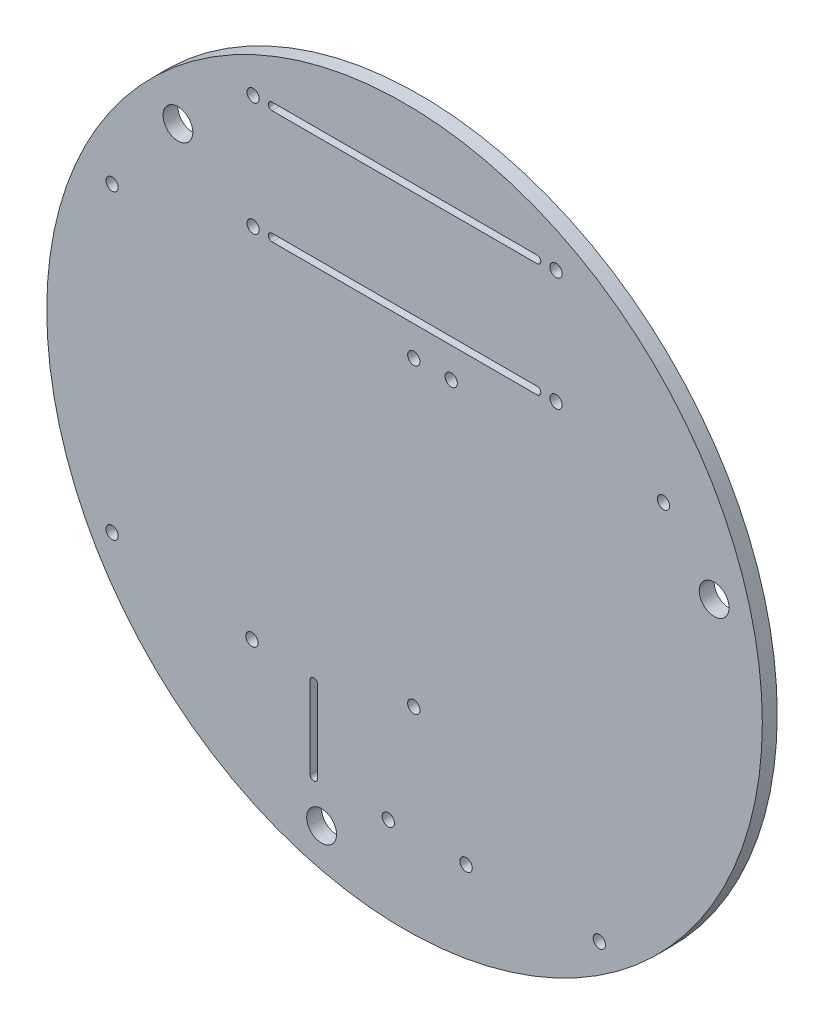
SolidWorks part; units mm, degrees
ref_plane "Plan de face" through (0, 0, 0) normal (0, 0, 1) x (1, 0, 0)
ref_plane "Plan de dessus" through (0, 0, 0) normal (0, 1, 0) x (1, 0, 0)
ref_plane "Plan de droite" through (0, 0, 0) normal (1, 0, 0) x (0, 0, -1)
sketch "Sketch1" plane through (0, 0, 0) normal (0, 0, 1) x (1, 0, 0)
  circle A0 centre (0, 0) radius 48
  dimension "D1" = 96
extrude "Boss-Extrude1" add sketch "Sketch1" along normal blind 2
sketch "Sketch3" plane through (0, 0, 0) normal (0, 0, -1) x (-1, 0, 0)
  line L0 (0, 0) -> (0, 43) construction
  line L1 (0, 0) -> (30.4056, 30.4056) construction
  circle A0 centre (0, 0) radius 43 construction
  circle A1 centre (30.4056, 30.4056) radius 2
  circle A2 centre (11.1292, -41.5348) radius 2
  circle A3 centre (-41.5348, 11.1292) radius 2
  point P6 (0, 0)
  point P13 (0, 0)
  dimension "D1" = 86
  dimension "D2" = 4
  dimension "D3" = 45
  dimension "D4" = 3
extrude "Cut-Extrude1" cut sketch "Sketch3" against normal through all contours A3 | A1 | A2
sketch "Sketch2" plane through (0, 0, 2) normal (0, 0, 1) x (1, 0, 0)
  line L0 (0, 40) -> (0, 22.24) construction
  line L1 (-21.58, 40) -> (21.58, 40) construction
  line L2 (-21.58, 40) -> (-21.58, 22.24) construction
  line L3 (-21.58, 22.24) -> (21.58, 22.24) construction
  line L4 (21.58, 40) -> (21.58, 22.24) construction
  line L5 (-21.58, 31.12) -> (21.58, 31.12) construction
  line L6 (20.5, 20.24) -> (20.5, -27.76) construction
  line L7 (5, 20.24) -> (36, 20.24) construction
  line L8 (5, 20.24) -> (5, -27.76) construction
  line L9 (5, -27.76) -> (36, -27.76) construction
  line L10 (36, 20.24) -> (36, -27.76) construction
  line L11 (-19, 20.24) -> (-19, -22.76) construction
  line L12 (-40.5, -22.76) -> (2.5, -22.76) construction
  line L13 (-40.5, -22.76) -> (-40.5, 20.24) construction
  line L14 (-40.5, 20.24) -> (2.5, 20.24) construction
  line L15 (2.5, -22.76) -> (2.5, 20.24) construction
  line L16 (-40.5, -1.26) -> (2.5, -1.26) construction
  line L17 (17.78, 23.5) -> (-17.78, 23.5) construction
  line L18 (17.78, 23) -> (-17.78, 23)
  line L19 (17.78, 24) -> (-17.78, 24)
  line L20 (17.78, 38.74) -> (-17.78, 38.74) construction
  line L21 (17.78, 39.24) -> (-17.78, 39.24)
  line L22 (17.78, 38.24) -> (-17.78, 38.24)
  circle A0 centre (20.32, 38.74) radius 0.825
  circle A1 centre (20.32, 23.5) radius 0.825
  circle A2 centre (-20.32, 23.5) radius 0.825
  circle A3 centre (-20.32, 38.74) radius 0.825
  circle A4 centre (34.74, 18.98) radius 0.825
  circle A5 centre (6.26, 18.98) radius 0.825
  circle A6 centre (-39.24, 18.98) radius 0.825
  circle A7 centre (1.24, 18.98) radius 0.825
  circle A8 centre (1.24, -21.5) radius 0.825
  circle A9 centre (-39.24, -21.5) radius 0.825
  arc A10 (17.78, 23) -> (17.78, 24) centre (17.78, 23.5) ccw
  arc A11 (-17.78, 24) -> (-17.78, 23) centre (-17.78, 23.5) ccw
  arc A12 (17.78, 39.24) -> (17.78, 38.24) centre (17.78, 38.74) cw
  arc A13 (-17.78, 38.24) -> (-17.78, 39.24) centre (-17.78, 38.74) cw
  point P9 (0, 31.12)
  point P46 (0, 23.5)
  point P55 (0, 38.74)
  dimension "D4" = 1.26
  dimension "D6" = 1.65
  dimension "D11" = 1.26
  dimension "D13" = 1.65
  dimension "D18" = 1.26
  dimension "D19" = 1.65
  dimension "D1" = 43.16
  dimension "D2" = 17.76
  dimension "D3" = 40
  dimension "D5" = 1.26
  dimension "D7" = 48
  dimension "D8" = 31
  dimension "D9" = 50
  dimension "D10" = 5
  dimension "D12" = 1.26
  dimension "D14" = 43
  dimension "D15" = 43
  dimension "D16" = 2.5
  dimension "D17" = 2
  dimension "D20" = 1
  dimension "D21" = 2.54
  dimension "D22" = 2.54
extrude "Cut-Extrude-Nano+Recto" cut sketch "Sketch2" against normal through all
sketch "Sketch4" plane through (0, 0, 0) normal (0, 0, -1) x (-1, 0, 0)
  line L0 (-27.39, -37.6) -> (-27.39, -22) construction
  line L1 (-27.39, -22) -> (-7, -22) construction
  line L2 (-7, -22) -> (-7, -37.6) construction
  line L3 (-7, -37.6) -> (-27.39, -37.6) construction
  line L4 (3.44, -37.6) -> (3.44, -24.56) construction
  line L5 (3.44, -24.56) -> (-7, -24.56) construction
  line L7 (-7, -37.6) -> (3.44, -37.6) construction
  line L8 (-17.195, -22) -> (-17.195, -37.6) construction
  line L9 (12.18, -36.34) -> (12.18, -25.34) construction
  line L12 (11.68, -36.34) -> (11.68, -25.34)
  line L13 (12.68, -36.34) -> (12.68, -25.34)
  circle A0 centre (-8.26, -36.34) radius 0.825
  circle A1 centre (2.18, -36.34) radius 0.825
  circle A2 centre (-26.13, -36.34) radius 0.825
  arc A7 (11.68, -36.34) -> (12.68, -36.34) centre (12.18, -36.34) ccw
  arc A8 (12.68, -25.34) -> (11.68, -25.34) centre (12.18, -25.34) ccw
  circle A9 centre (20.48, -24.54) radius 0.825
  point P18 (12.18, -30.84)
  dimension "D7" = 1.26
  dimension "D11" = 1.65
  dimension "D12" = 1.65
  dimension "D13" = 11
  dimension "D14" = 0.5
  dimension "D16" = 0.8
  dimension "D18" = 1.65
  dimension "D1" = 20.39
  dimension "D2" = 15.6
  dimension "D3" = 13.04
  dimension "D4" = 10.44
  dimension "D5" = 7
  dimension "D6" = 22
  dimension "D8" = 1.26
  dimension "D9" = 1.26
  dimension "D10" = 1.26
  dimension "D15" = 10
  dimension "D17" = 8.3
extrude "Cut-Extrude-Verso" cut sketch "Sketch4" against normal through all
